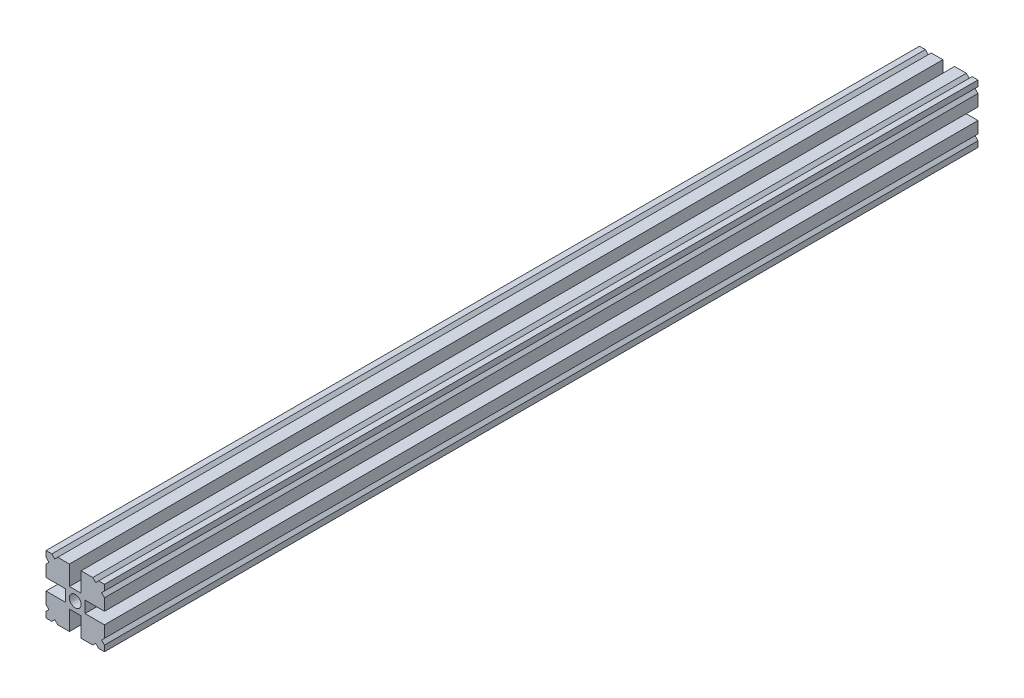
SolidWorks part; units mm, degrees
ref_plane "Front Plane" through (0, 0, 0) normal (0, 0, 1) x (1, 0, 0)
ref_plane "Top Plane" through (0, 0, 0) normal (0, 1, 0) x (1, 0, 0)
ref_plane "Right Plane" through (0, 0, 0) normal (1, 0, 0) x (0, 0, -1)
sketch "Sketch1" plane through (0, 0, 0) normal (0, 0, 1) x (1, 0, 0)
  line L0 (-1.5, 7.5) -> (1.5, 7.5) construction
  line L1 (-7.5, 7.5) -> (7.5, 7.5) construction
  line L2 (-7.5, 7.5) -> (-7.5, -7.5) construction
  line L3 (-7.5, -7.5) -> (7.5, -7.5) construction
  line L4 (7.5, 7.5) -> (7.5, -7.5) construction
  line L5 (-7.5, 7.5) -> (7.5, -7.5) construction
  line L6 (-7.5, -7.5) -> (7.5, 7.5) construction
  line L7 (-7.5, 7.5) -> (-6, 7.5)
  line L8 (7.5, 7.5) -> (6, 7.5)
  line L9 (-6, 7.5) -> (-5.25, 6.75)
  line L10 (-5.25, 6.75) -> (-4.5, 7.5)
  line L11 (-4.5, 7.5) -> (-1.5, 7.5)
  line L12 (-1.5, 7.5) -> (-1.5, 2.5)
  line L13 (-1.5, 2.5) -> (1.5, 2.5)
  line L14 (1.5, 2.5) -> (1.5, 7.5)
  line L15 (1.5, 7.5) -> (4.5, 7.5)
  line L16 (4.5, 7.5) -> (5.25, 6.75)
  line L17 (5.25, 6.75) -> (6, 7.5)
  line L18 (7.5, 7.5) -> (7.5, 6)
  line L19 (7.5, 6) -> (6.75, 5.25)
  line L20 (6.75, 5.25) -> (7.5, 4.5)
  line L21 (7.5, 4.5) -> (7.5, 1.5)
  line L22 (7.5, 1.5) -> (2.5, 1.5)
  line L23 (2.5, 1.5) -> (2.5, -1.5)
  line L24 (2.5, -1.5) -> (7.5, -1.5)
  line L25 (7.5, -1.5) -> (7.5, -4.5)
  line L26 (6.75, -5.25) -> (7.5, -6)
  line L27 (7.5, -4.5) -> (6.75, -5.25)
  line L28 (7.5, -7.5) -> (7.5, -6)
  line L29 (7.5, -7.5) -> (6, -7.5)
  line L30 (6, -7.5) -> (5.25, -6.75)
  line L31 (5.25, -6.75) -> (4.5, -7.5)
  line L32 (4.5, -7.5) -> (1.5, -7.5)
  line L33 (1.5, -7.5) -> (1.5, -2.5)
  line L34 (1.5, -2.5) -> (-1.5, -2.5)
  line L35 (-1.5, -2.5) -> (-1.5, -7.5)
  line L36 (-1.5, -7.5) -> (-4.5, -7.5)
  line L37 (-5.25, -6.75) -> (-6, -7.5)
  line L38 (-4.5, -7.5) -> (-5.25, -6.75)
  line L39 (-7.5, -7.5) -> (-6, -7.5)
  line L40 (-7.5, -7.5) -> (-7.5, -6)
  line L41 (-7.5, -6) -> (-6.75, -5.25)
  line L42 (-6.75, -5.25) -> (-7.5, -4.5)
  line L43 (-7.5, -4.5) -> (-7.5, -1.5)
  line L44 (-7.5, -1.5) -> (-2.5, -1.5)
  line L45 (-2.5, -1.5) -> (-2.5, 1.5)
  line L46 (-2.5, 1.5) -> (-7.5, 1.5)
  line L47 (-7.5, 1.5) -> (-7.5, 4.5)
  line L48 (-6.75, 5.25) -> (-7.5, 6)
  line L49 (-7.5, 4.5) -> (-6.75, 5.25)
  line L50 (-7.5, 7.5) -> (-7.5, 6)
  circle A0 centre (0, 0) radius 1.5
  point P0 (0, 0)
  point P8 (0, 7.5)
  point P56 (0, 0)
  dimension "D8" = 3
  dimension "D1" = 15
  dimension "D2" = 3
  dimension "D3" = 1.5
  dimension "D4" = 5
  dimension "D5" = 1.5
  dimension "D6" = 3
  dimension "D7" = 4
extrude "Boss-Extrude1" add sketch "Sketch1" along normal blind 224
